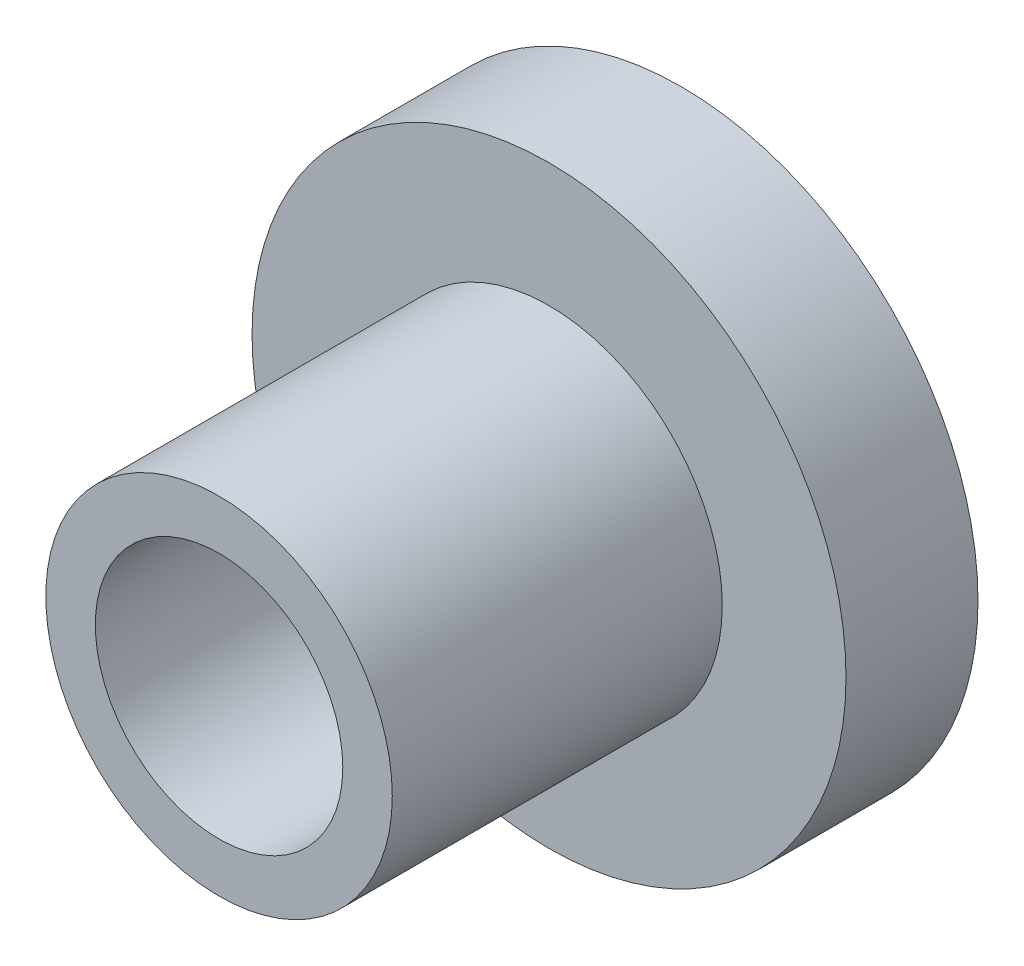
SolidWorks part; units mm, degrees
material "PLA"
ref_plane "Alzado" through (0, 0, 0) normal (0, 0, 1) x (1, 0, 0)
ref_plane "Planta" through (0, 0, 0) normal (0, 1, 0) x (1, 0, 0)
ref_plane "Vista lateral" through (0, 0, 0) normal (1, 0, 0) x (0, 0, -1)
sketch "Sketch1" plane through (0, 0, 0) normal (0, 0, 1) x (1, 0, 0)
  circle A0 centre (0, 0) radius 1.875
  circle A1 centre (0, 0) radius 4.5
  dimension "D1" = 3.75
  dimension "D2" = 9
extrude "Boss-Extrude1" add sketch "Sketch1" along normal blind 2
sketch "Sketch2" plane through (0, 0, 2) normal (0, 0, 1) x (1, 0, 0)
  circle A0 centre (0, 0) radius 1.875
  circle A1 centre (0, 0) radius 2.625
  dimension "D1" = 5.25
  dimension "D2" = 3.75
extrude "Boss-Extrude2" add sketch "Sketch2" along normal blind 5
